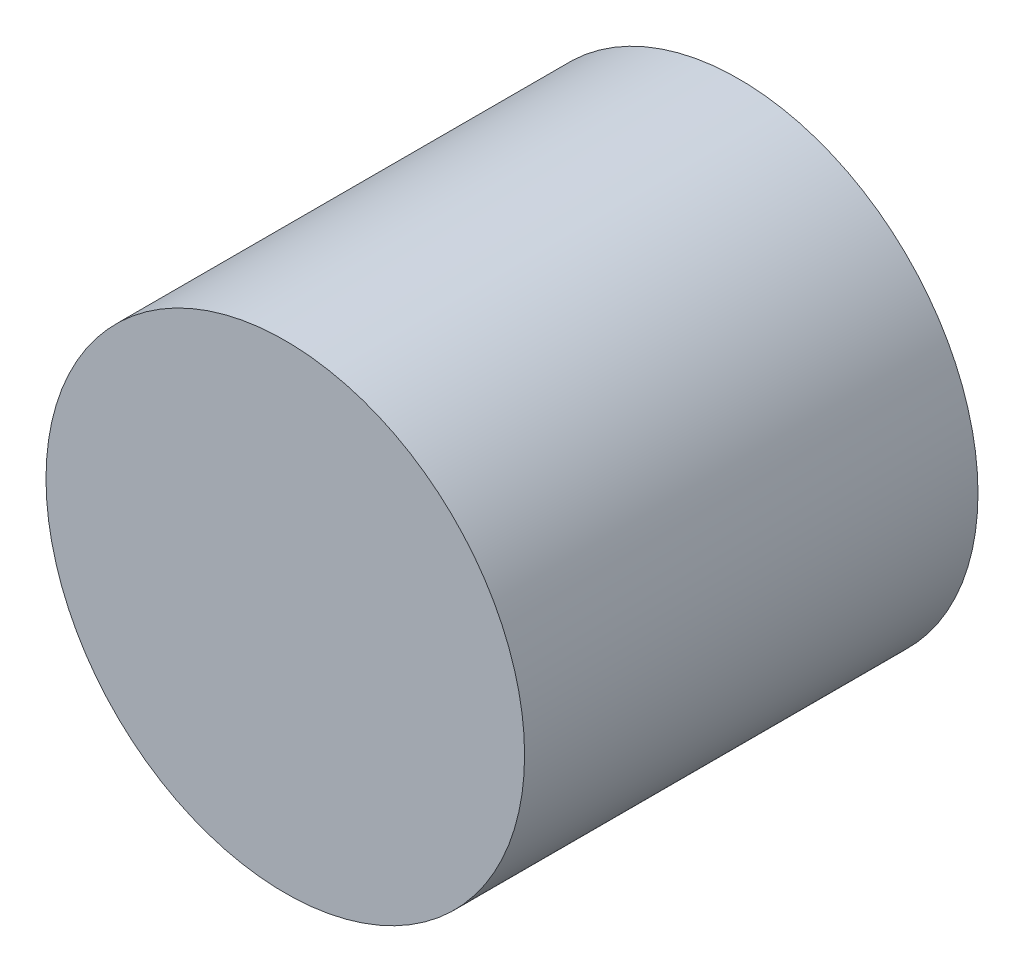
SolidWorks part; units mm, degrees
ref_plane "Front" through (0, 0, 0) normal (0, 0, 1) x (1, 0, 0)
ref_plane "Top" through (0, 0, 0) normal (0, 1, 0) x (1, 0, 0)
ref_plane "Right" through (0, 0, 0) normal (1, 0, 0) x (0, 0, -1)
other "Configuration Table"
sketch "Sketch1" plane through (0, 0, 0) normal (0, 0, 1) x (1, 0, 0)
  circle A0 centre (0, 0) radius 19
  dimension "D1" = 38
extrude "Base-Extrude" add sketch "Sketch1" along normal blind 36
scale "Scale1" scale about centroid uniform scaling yes scale factor 2.5
scale "Scale2" scale about centroid uniform scaling yes scale factor 1.2
